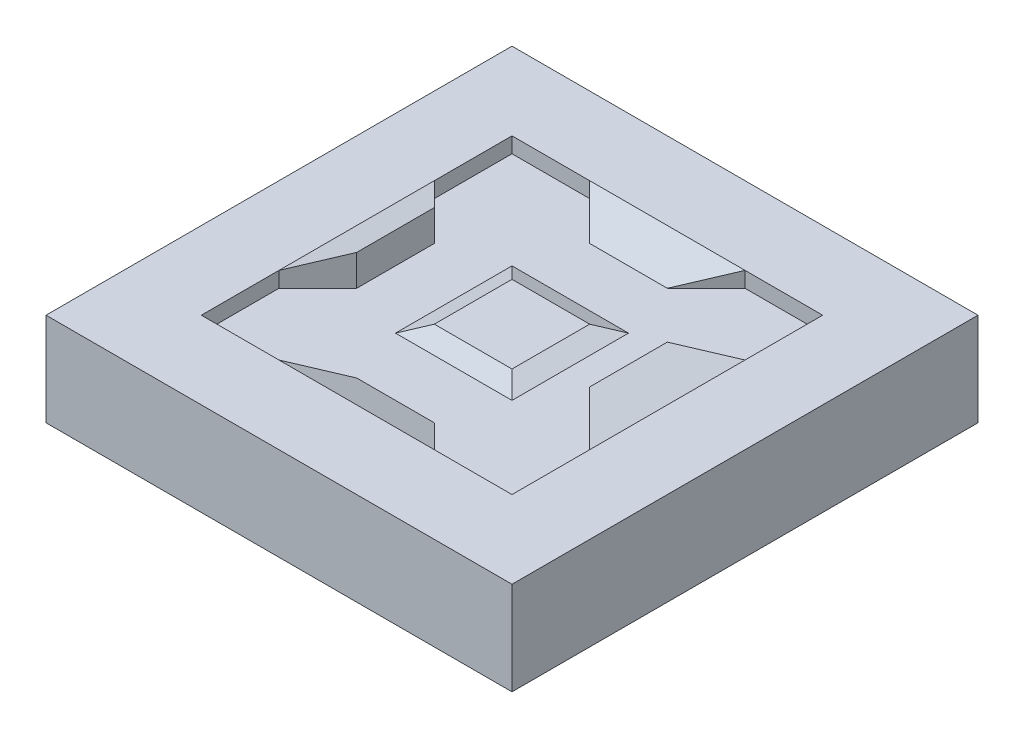
SolidWorks part; units mm, degrees
ref_plane "Front Plane" through (0, 0, 0) normal (0, 0, 1) x (1, 0, 0)
ref_plane "Top Plane" through (0, 0, 0) normal (0, 1, 0) x (1, 0, 0)
ref_plane "Right Plane" through (0, 0, 0) normal (1, 0, 0) x (0, 0, -1)
sketch "Sketch1" plane through (0, 0, 0) normal (0, 1, 0) x (1, 0, 0)
  line L1 (-1524, 1524) -> (1524, 1524)
  line L2 (-1524, 1524) -> (-1524, -1524)
  line L3 (-1524, -1524) -> (1524, -1524)
  line L4 (1524, 1524) -> (1524, -1524)
  dimension "D1" = 1524
  dimension "D2" = 1524
  dimension "D3" = 1524
  dimension "D4" = 1524
extrude "Extrude1" add sketch "Sketch1" against normal blind 508 and the other way blind 101.6
sketch "Sketch2" plane through (0, 101.6, 0) normal (0, 1, 0) x (1, 0, 0)
  line L1 (-1016, 1016) -> (1016, 1016)
  line L2 (-1016, 1016) -> (-1016, -1016)
  line L3 (-1016, -1016) -> (1016, -1016)
  line L4 (1016, 1016) -> (1016, -1016)
  dimension "D1" = 1016
  dimension "D2" = 1016
  dimension "D3" = 1016
  dimension "D4" = 1016
extrude "Extrude2" cut sketch "Sketch2" against normal blind 101.6
sketch "Sketch3" plane through (0, 0, 0) normal (0, 1, 0) x (1, 0, 0)
  line L1 (-381, 381) -> (381, 381)
  line L2 (-381, 381) -> (-381, -381)
  line L3 (-381, -381) -> (381, -381)
  line L4 (381, 381) -> (381, -381)
  dimension "D1" = 381
  dimension "D2" = 381
  dimension "D3" = 381
  dimension "D4" = 381
extrude "Extrude3" add sketch "Sketch3" along normal blind 50.8 draft 68.199
sketch "Sketch4" plane through (0, 0, 0) normal (0, 1, 0) x (1, 0, 0)
  line L0 (1016, 1016) -> (-1016, 1016) construction
  line L1 (-253.9999, 762) -> (-507.9999, 1016)
  line L2 (1016, 1016) -> (-1016, 1016) construction
  line L3 (253.9999, 762) -> (-253.9999, 762)
  line L4 (253.9999, 762) -> (507.9999, 1016)
  line L5 (-507.9999, 1016) -> (507.9999, 1016)
  line L6 (-253.9999, -762) -> (253.9999, -762)
  line L7 (-1016, -1016) -> (1016, -1016) construction
  line L9 (-253.9999, -762) -> (-507.9999, -1016)
  line L10 (-507.9999, -1016) -> (507.9999, -1016)
  line L11 (-1016, -1016) -> (1016, -1016) construction
  line L12 (507.9999, -1016) -> (253.9999, -762)
  dimension "D1" = 254
  dimension "D2" = 254
extrude "Extrude6" add sketch "Sketch4" along normal blind 101.6
sketch "Sketch6" plane through (0, 0, 0) normal (1, 0, 0) x (0, 0, -1)
  line L0 (762, 101.6) -> (762, 0)
  line L1 (1016, 0) -> (-1016, 0) construction
  line L2 (762, 101.6) -> (762, 0) construction
  line L3 (762, 0) -> (1016, 101.6)
  line L4 (1016, 101.6) -> (762, 101.6)
  line L5 (-1016, 101.6) -> (-762, 0)
  line L6 (-1016, 0) -> (-762, 0) construction
  line L7 (-762, 0) -> (-762, 101.6)
  line L8 (-1016, 101.6) -> (-762, 101.6) construction
  line L9 (-762, 101.6) -> (-762, 0) construction
  line L10 (-762, 101.6) -> (-1016, 101.6)
extrude "Extrude7" cut sketch "Sketch6" against normal blind 508 and the other way blind 508
sketch "Sketch8" plane through (0, 0, 0) normal (0, 1, 0) x (1, 0, 0)
  line L0 (1016, -1016) -> (1016, 1016) construction
  line L1 (762, 253.9999) -> (1016, 507.9999)
  line L2 (1016, -1016) -> (1016, 1016) construction
  line L3 (762, -253.9999) -> (762, 253.9999)
  line L4 (762, -253.9999) -> (1016, -507.9999)
  line L5 (1016, -507.9999) -> (1016, 507.9999)
  line L6 (-762, 253.9999) -> (-762, -253.9999)
  line L7 (-1016, 1016) -> (-1016, -1016) construction
  line L8 (-762, -253.9999) -> (-1016, -507.9999)
  line L9 (-1016, 1016) -> (-1016, -1016) construction
  line L10 (-1016, -507.9999) -> (-1016, 507.9999)
  line L11 (-1016, 507.9999) -> (-762, 253.9999)
  dimension "D1" = 254
  dimension "D2" = 254
extrude "Extrude8" add sketch "Sketch8" along normal blind 203.2
sketch "Sketch10" plane through (0, 0, 0) normal (0, 0, 1) x (1, 0, 0)
  line L0 (-1016, 203.2) -> (-1016, 101.6)
  line L1 (-1016, 101.6) -> (-762, 203.2)
  line L2 (-762, 203.2) -> (-1016, 203.2)
  line L3 (1016, 203.2) -> (1016, 101.6)
  line L4 (1016, 101.6) -> (762, 203.2)
  line L5 (762, 203.2) -> (1016, 203.2)
extrude "Extrude12" cut sketch "Sketch10" against normal blind 508 and the other way blind 508
